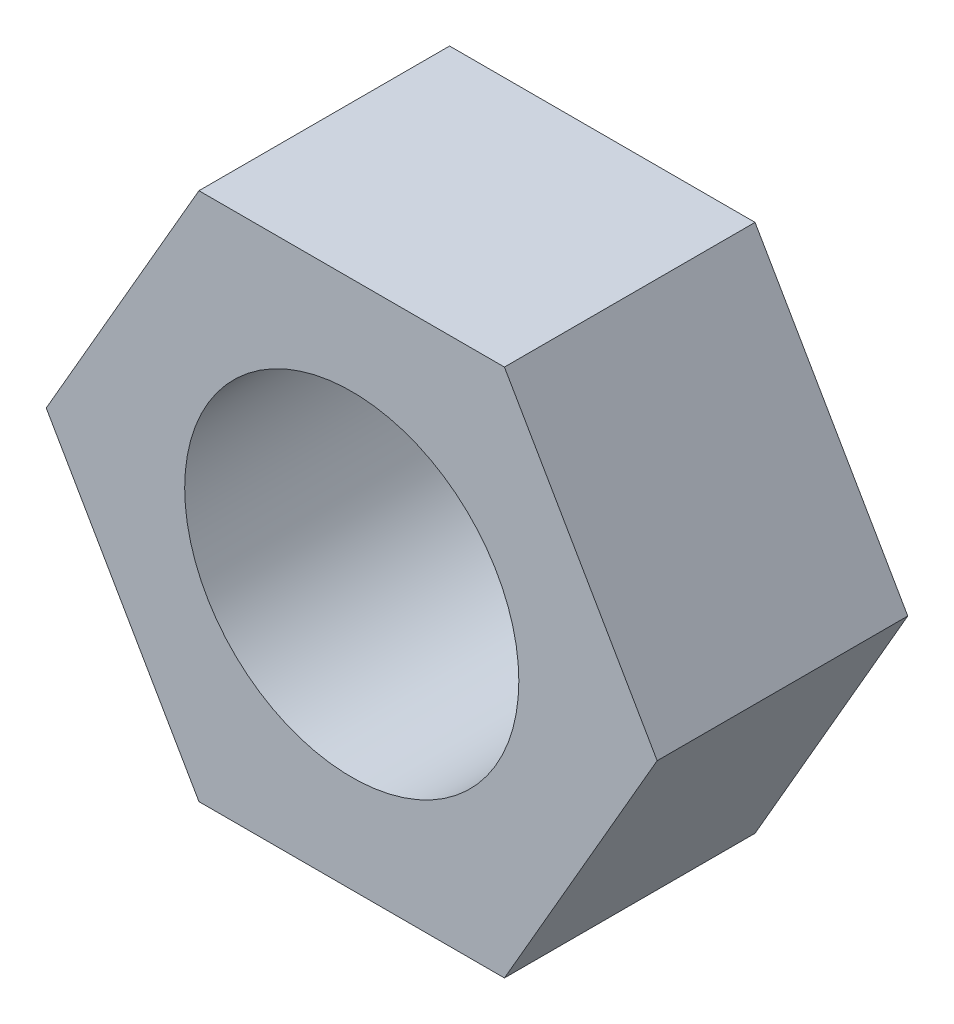
SolidWorks part; units mm, degrees
ref_plane "前视基准面" through (0, 0, 0) normal (0, 0, 1) x (1, 0, 0)
ref_plane "上视基准面" through (0, 0, 0) normal (0, 1, 0) x (1, 0, 0)
ref_plane "右视基准面" through (0, 0, 0) normal (1, 0, 0) x (0, 0, -1)
sketch "草图1" plane through (0, 0, 0) normal (0, 0, 1) x (1, 0, 0)
  line L0 (-5.4848, 9.5) -> (5.4848, 9.5)
  line L3 (5.4848, -9.5) -> (-5.4848, -9.5)
  line L6 (-5.4848, 9.5) -> (-10.9697, 0)
  line L7 (-10.9697, 0) -> (-5.4848, -9.5)
  line L8 (5.4848, -9.5) -> (10.9697, 0)
  line L9 (10.9697, 0) -> (5.4848, 9.5)
extrude "拉伸1" add sketch "草图1" along normal blind 9
hole_wizard "M12x1.25 螺纹孔1" positions "3D草图1" profile "草图2" tap size "M12x1.25" standard "ISO"
sketch3d "3D草图1"
  line L0 (5.4848, 9.5, 9) -> (-5.4848, 9.5, 9) construction
  point P0 (0, 0, 0)
  point P4 (0.0025, 0, 9)
  dimension "D1" = 9.5
sketch "草图2" plane through (0.0025, 0, 9) normal (1, 0, 0) x (0, -1, 0)
  line L0 (0, 0) -> (0, 30.9946)
  line L1 (0, 30.9946) -> (5.4, 27.75)
  line L2 (5.4, 27.75) -> (5.4, 24)
  line L3 (5.4, 24) -> (6, 24)
  line L4 (6, 24) -> (6, 0)
  line L5 (6, 0) -> (0, 0)
  line L10 (0, 30.9946) -> (-5.4, 27.75) construction
  line L11 (0, -6.35) -> (0, 107.95) construction
  dimension "蹟恇謂郰芛眻噤" = 10.8
  dimension "蹟恇謂郰芛旮僅" = 27.75
  dimension "蹟恇翋眻噤" = 12
  dimension "蹟恇旮僅" = 24
  dimension "絳芛褒僅" = 118
